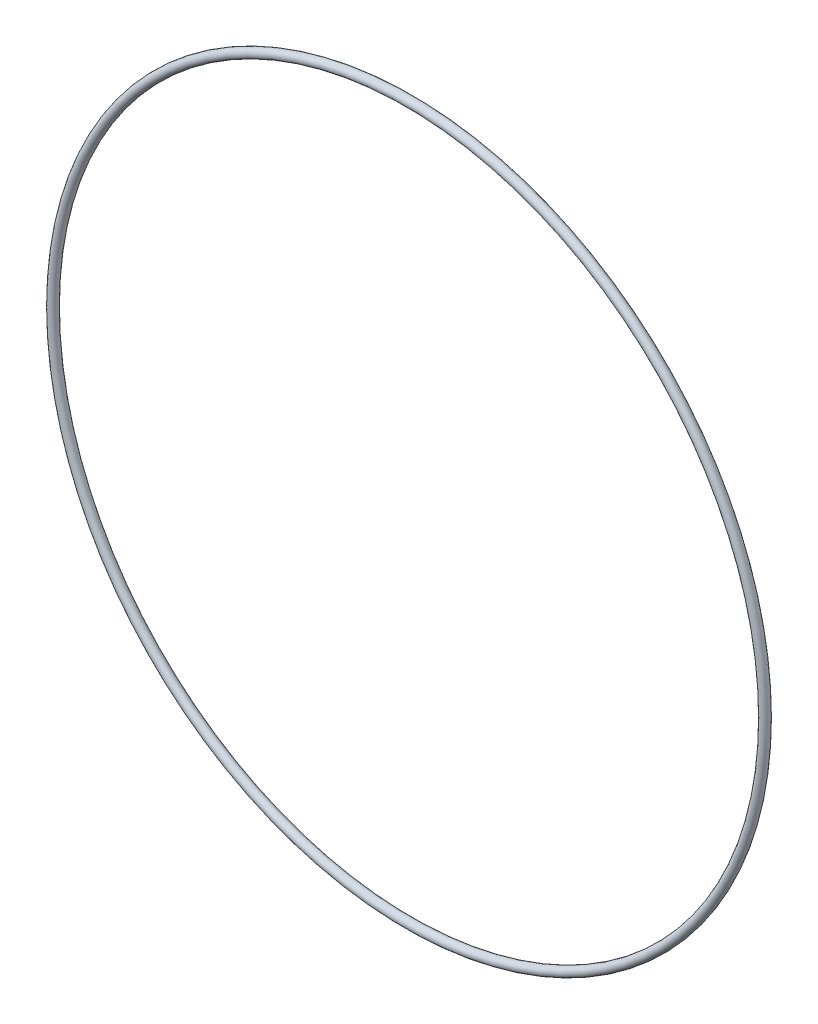
SolidWorks part; units mm, degrees
ref_plane "Front Plane" through (0, 0, 0) normal (0, 0, 1) x (1, 0, 0)
ref_plane "Top Plane" through (0, 0, 0) normal (0, 1, 0) x (1, 0, 0)
ref_plane "Right Plane" through (0, 0, 0) normal (1, 0, 0) x (0, 0, -1)
sketch "Sketch1" plane through (0, 0, 0) normal (0, 1, 0) x (1, 0, 0)
  line L0 (0, 0) -> (470, 0.3844) construction
  line L1 (470, 23.8045) -> (470, -21.2134) construction
  circle A0 centre (0, 0) radius 6
  circle A1 centre (0, 0) radius 5
  point P7 (0, 0)
  dimension "D1" = 12
  dimension "D2" = 10
  dimension "D3" = 470
revolve "Revolve1" add sketch "Sketch1" angle 360 about L1
